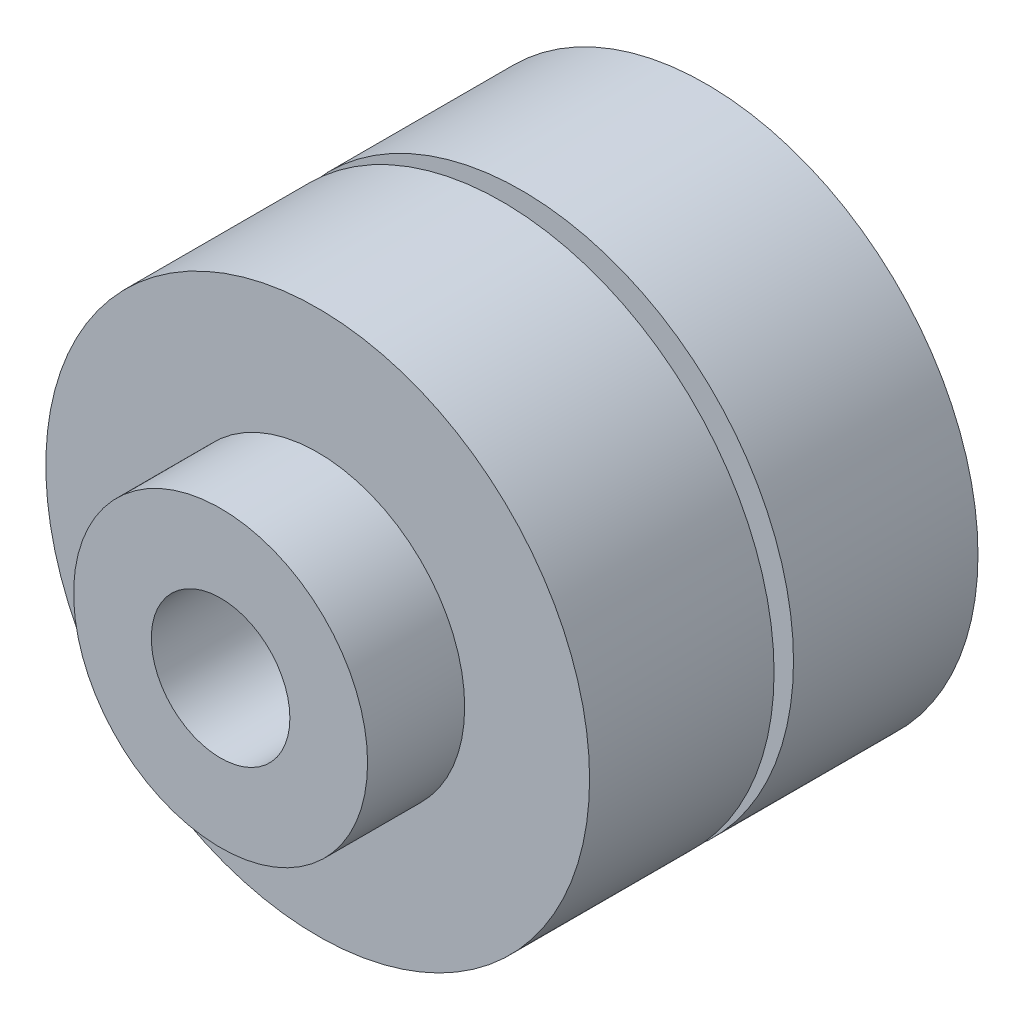
SolidWorks part; units mm, degrees
ref_plane "Front Plane" through (0, 0, 0) normal (0, 0, 1) x (1, 0, 0)
ref_plane "Top Plane" through (0, 0, 0) normal (0, 1, 0) x (1, 0, 0)
ref_plane "Right Plane" through (0, 0, 0) normal (1, 0, 0) x (0, 0, -1)
sketch "Sketch1" plane through (0, 0, 0) normal (0, 1, 0) x (1, 0, 0)
  line L0 (-5, 60) -> (-5, 30)
  line L1 (-5, 30) -> (-50, 30)
  line L2 (-50, 30) -> (-50, -30)
  line L3 (-50, -30) -> (-17.8412, -30)
  line L4 (-17.8412, -30) -> (-17.8412, -75)
  line L5 (-17.8412, -75) -> (-37.8412, -75)
  line L6 (-37.8412, -75) -> (-37.8412, -50)
  line L7 (-37.8412, -50) -> (-70, -50)
  line L8 (-70, -50) -> (-70, -2.5)
  line L9 (-70, 50) -> (-25, 50)
  line L10 (-25, 50) -> (-25, 60)
  line L11 (-25, 60) -> (-5, 60)
  line L12 (-27.5, 30) -> (-27.5, 50) construction
  line L13 (-50, 0) -> (-70, 0) construction
  line L14 (-33.9206, -30) -> (-33.9206, -50) construction
  line L15 (-37.8412, -62.5) -> (-17.8412, -62.5) construction
  line L16 (-25, 55) -> (-5, 55) construction
  line L17 (0, -16.413) -> (0, 22.0313) construction
  line L18 (-70, -2.5) -> (-55, -2.5)
  line L19 (-55, -2.5) -> (-55, 2.5)
  line L20 (-55, 2.5) -> (-70, 2.5)
  line L21 (-70, 2.5) -> (-70, 50)
  point P27 (-55, 0)
  point P30 (-55.1412, 0)
  point P31 (-55, -2.3781)
  dimension "D1" = 17.8412
  dimension "D2" = 60
  dimension "D3" = 20
  dimension "D4" = 5
  dimension "D5" = 30
  dimension "D6" = 45
  dimension "D7" = 50
  dimension "D8" = 5
  dimension "D9" = 5
revolve "Revolve1" add sketch "Sketch1" angle 360 about L17
equation "\"stroke\"= 30mm"
equation "\"D1@Sketch1\"=sqr(0.001/pi)*1000"
equation "\"D2@Sketch1\"=\"stroke\"*2"
equation "\"thiched\"= 20mm"
equation "\"D3@Sketch1\"=\"thiched\""
equation "\"D4@Sketch1\"=10/2"
equation "\"D6@Sketch1\"=35+10"
